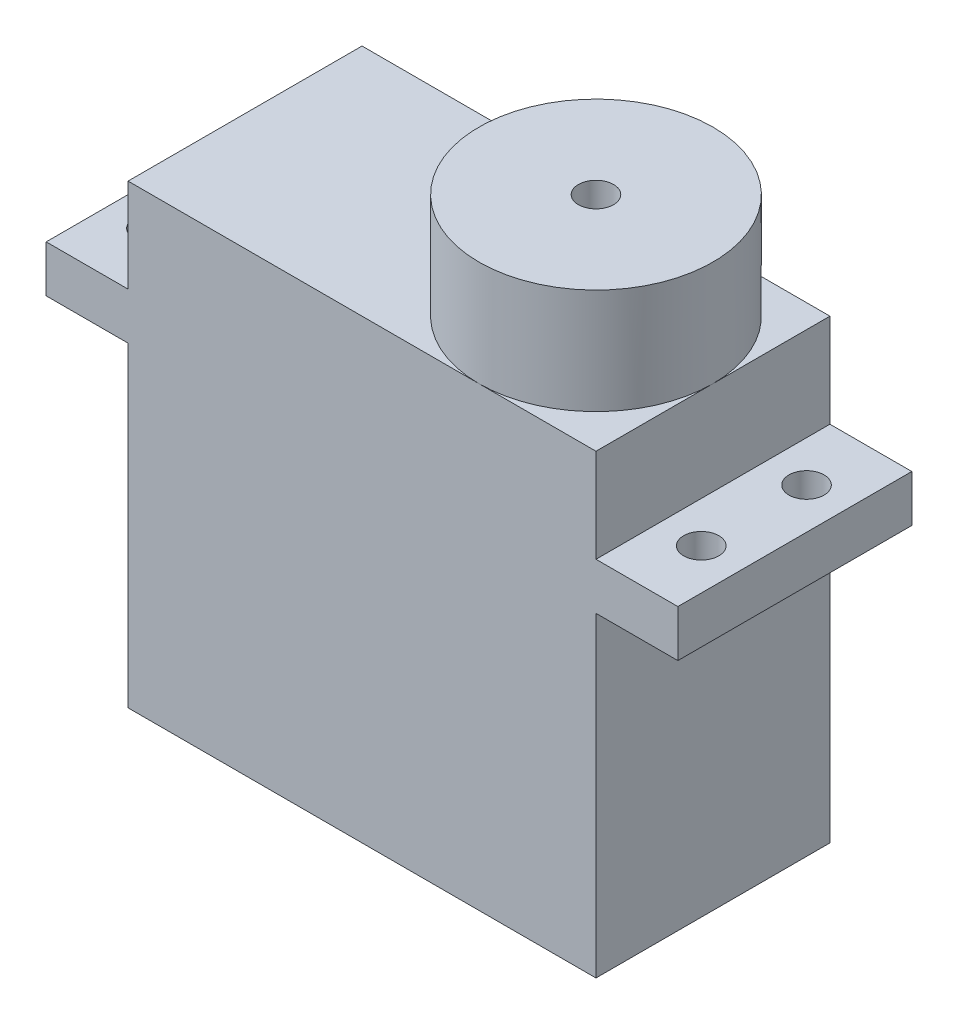
SolidWorks part; units mm, degrees
material "ABS"
ref_plane "Спереди" through (0, 0, 0) normal (0, 0, 1) x (1, 0, 0)
ref_plane "Сверху" through (0, 0, 0) normal (0, 1, 0) x (1, 0, 0)
ref_plane "Справа" through (0, 0, 0) normal (1, 0, 0) x (0, 0, -1)
sketch "Эскиз1" plane through (0, 0, 0) normal (0, 1, 0) x (1, 0, 0)
  line L1 (-20, -10) -> (20, -10)
  line L2 (-20, -10) -> (-20, 10)
  line L3 (-20, 10) -> (20, 10)
  line L4 (20, -10) -> (20, 10)
  line L5 (-20, -10) -> (20, 10) construction
  line L6 (-20, 10) -> (20, -10) construction
  point P0 (0, 0)
  dimension "D1" = 40
  dimension "D2" = 20
extrude "Бобышка-Вытянуть1" add sketch "Эскиз1" along normal blind 39
sketch "Эскиз2" plane through (20, 0, 0) normal (1, 0, 0) x (0, 0, -1)
  line L0 (-10, 0) -> (-10, 31) construction
  line L1 (-10, 39) -> (-10, 0) construction
  line L2 (-10, 31) -> (-10, 27)
  line L3 (-10, 31) -> (10, 31)
  line L4 (10, 39) -> (10, 0) construction
  line L5 (10, 31) -> (10, 27)
  line L6 (10, 27) -> (-10, 27)
  dimension "D1" = 31
  dimension "D2" = 4
extrude "Бобышка-Вытянуть2" add sketch "Эскиз2" along normal blind 7
sketch "Эскиз3" plane through (0, 31, 0) normal (0, 1, 0) x (1, 0, 0)
  line L0 (27, 0) -> (20, 0) construction
  line L1 (27, 10) -> (27, -10) construction
  line L2 (20, 10) -> (20, -10) construction
  line L3 (23.5, 0) -> (23.5, 4.5) construction
  line L4 (23.5, 0) -> (23.5, -4.5) construction
  circle A0 centre (23.5, 4.5) radius 1.5
  circle A1 centre (23.5, -4.5) radius 1.5
  dimension "D1" = 3
  dimension "D2" = 3
  dimension "D3" = 4.5
  dimension "D4" = 4.5
extrude "Вырез-Вытянуть1" cut sketch "Эскиз3" against normal blind 4
sketch "Эскиз4" plane through (0, 0, 10) normal (0, 0, 1) x (1, 0, 0)
  line L0 (20, 31) -> (-20, 31) construction
  line L1 (-20, 39) -> (-20, 0) construction
  line L2 (-20, 31) -> (-27, 31)
  line L3 (-27, 31) -> (-27, 27)
  line L4 (-27, 27) -> (-20, 27)
  line L5 (-20, 27) -> (-20, 31)
  dimension "D1" = 7
  dimension "D2" = 4
extrude "Бобышка-Вытянуть3" add sketch "Эскиз4" against normal up to surface (20 mm away) up to face at (12.625, 26.4375, -10)
sketch "Эскиз5" plane through (0, 31, 0) normal (0, 1, 0) x (1, 0, 0)
  line L0 (23.5, -4.5) -> (-27, -4.5) construction
  line L1 (-27, 10) -> (-27, -10) construction
  line L2 (23.5, 4.5) -> (-27, 4.5) construction
  line L3 (-20, 0) -> (-27, 0) construction
  line L4 (-20, 10) -> (-20, -10) construction
  line L5 (-23.5, 0) -> (-23.5, -4.5) construction
  line L6 (-23.5, 0) -> (-23.5, 4.5) construction
  circle A0 centre (-23.5, -4.5) radius 1.5
  circle A1 centre (-23.5, 4.5) radius 1.5
  dimension "D1" = 3
  dimension "D2" = 3
extrude "Вырез-Вытянуть2" cut sketch "Эскиз5" against normal blind 4
sketch "Эскиз6" plane through (0, 39, 0) normal (0, 1, 0) x (1, 0, 0)
  line L0 (20, 0) -> (10, 0) construction
  line L1 (20, -10) -> (20, 10) construction
  circle A0 centre (10, 0) radius 10
  dimension "D1" = 10
extrude "Бобышка-Вытянуть4" add sketch "Эскиз6" along normal blind 9
sketch "Эскиз7" plane through (0, 48, 0) normal (0, 1, 0) x (1, 0, 0)
  circle A0 centre (10, 0) radius 1.5
  dimension "D1" = 3
extrude "Вырез-Вытянуть3" cut sketch "Эскиз7" against normal blind 6
